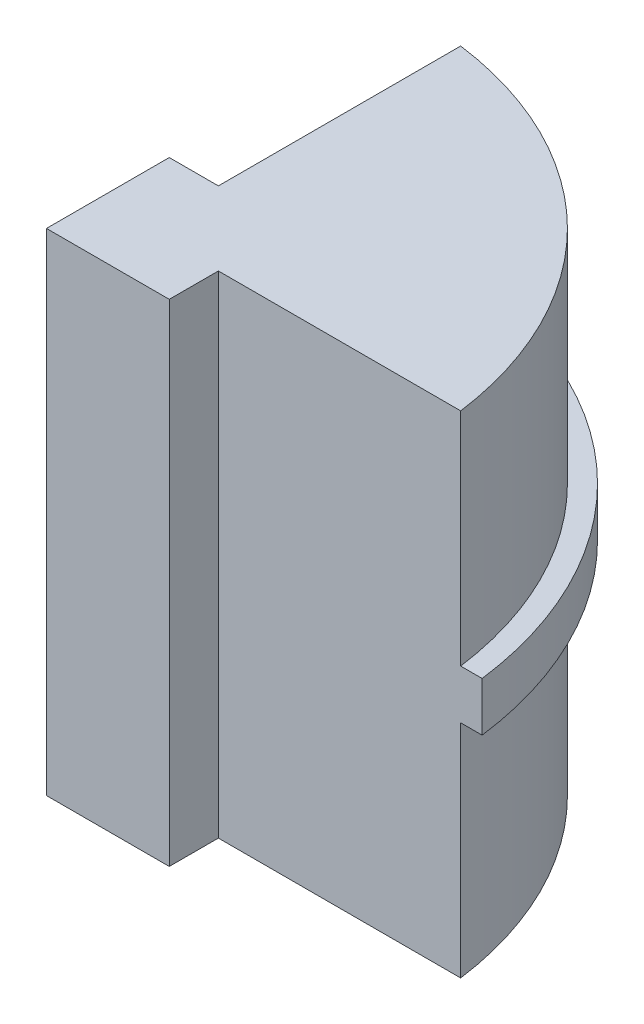
SolidWorks part; units mm, degrees
ref_plane "Front Plane" through (0, 0, 0) normal (0, 0, 1) x (1, 0, 0)
ref_plane "Top Plane" through (0, 0, 0) normal (0, 1, 0) x (1, 0, 0)
ref_plane "Right Plane" through (0, 0, 0) normal (1, 0, 0) x (0, 0, -1)
sketch "Sketch2" plane through (0, 0, 0) normal (0, 1, 0) x (1, 0, 0)
  line L0 (-78.383, -48.6502) -> (-78.383, -23.6502)
  line L3 (-78.383, -48.6502) -> (-53.383, -48.6502)
  line L6 (-78.383, -23.6502) -> (-68.383, -23.6502)
  line L7 (-53.383, -48.6502) -> (-53.383, -38.6502)
  line L8 (-68.383, -23.6502) -> (-68.383, 25.6802)
  line L9 (-53.383, -38.6502) -> (-4.0527, -38.6502)
  arc A0 (-4.0527, -38.6502) -> (-68.383, 25.6802) centre (-78.383, -48.6502) ccw
extrude "Boss-Extrude1" add sketch "Sketch2" along normal blind 100
ref_plane "Plane1" through (0, 50, 0) normal (0, -1, 0) x (-1, 0, 0)
sketch "Sketch3" plane through (0, 50, 0) normal (0, -1, 0) x (-1, 0, 0)
  line L3 (68.383, 25.6802) -> (68.383, 30.0499)
  line L4 (4.0527, -38.6502) -> (-0.317, -38.6502)
  arc A0 (68.383, 25.6802) -> (4.0527, -38.6502) centre (78.383, -48.6502) ccw
  arc A1 (68.383, 30.0499) -> (-0.317, -38.6502) centre (78.383, -48.6502) ccw
extrude "Boss-Extrude2" add sketch "Sketch3" along normal mid plane 10
